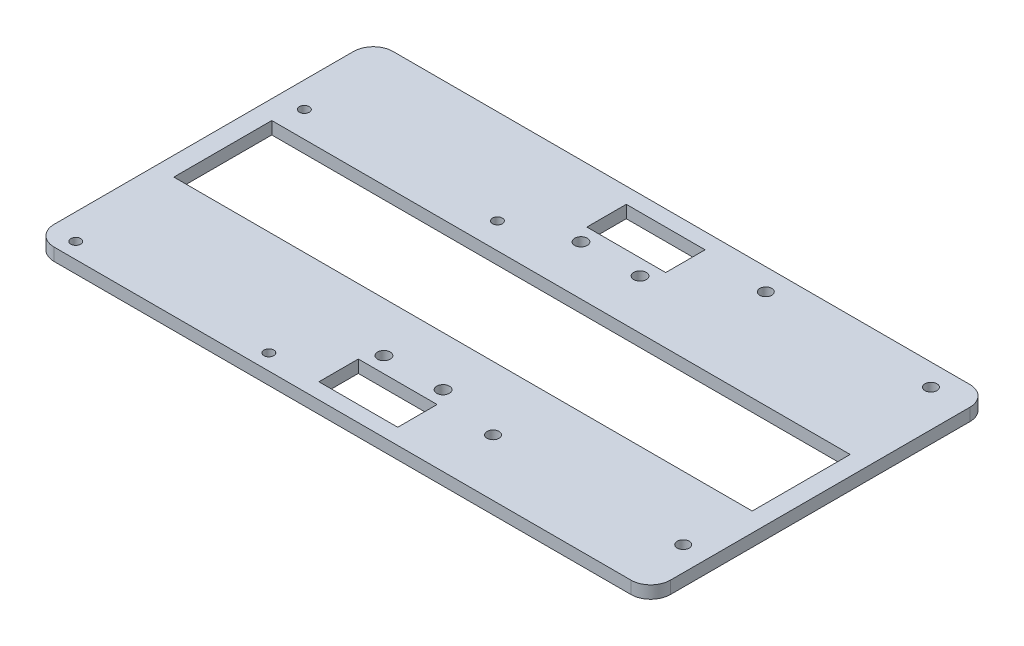
SolidWorks part; units mm, degrees
ref_plane "Front Plane" through (0, 0, 0) normal (0, 0, 1) x (1, 0, 0)
ref_plane "Top Plane" through (0, 0, 0) normal (0, 1, 0) x (1, 0, 0)
ref_plane "Right Plane" through (0, 0, 0) normal (1, 0, 0) x (0, 0, -1)
sketch "Sketch1" plane through (0, 0, 0) normal (0, 1, 0) x (1, 0, 0)
  line L1 (-78.2, 43) -> (78.2, 43)
  line L2 (-78.2, 43) -> (-78.2, -43)
  line L3 (-78.2, -43) -> (78.2, -43)
  line L4 (78.2, 43) -> (78.2, -43)
  line L5 (-78.2, 43) -> (78.2, -43) construction
  line L6 (-78.2, -43) -> (78.2, 43) construction
  point P0 (0, 0)
  dimension "D1" = 156.4
  dimension "D2" = 86
extrude "Boss-Extrude1" add sketch "Sketch1" along normal blind 3.175
sketch "Sketch3" plane through (0, 0, 0) normal (0, -1, 0) x (1, 0, 0)
  circle A0 centre (-22.7, -19) radius 1.25 construction
  circle A1 centre (-71.7, -19) radius 1.25 construction
  circle A2 centre (-71.7, 39) radius 1.25 construction
  circle A3 centre (-22.7, 39) radius 1.25 construction
  circle A4 centre (72.025, 28.575) radius 1.524 construction
  circle A5 centre (23.765, 28.575) radius 1.524 construction
  circle A6 centre (68.85, -37.465) radius 1.524 construction
  circle A7 centre (26.94, -37.465) radius 1.524 construction
  circle A8 centre (-22.7, -19) radius 1.25
  circle A9 centre (-71.7, -19) radius 1.25
  circle A10 centre (-71.7, 39) radius 1.25
  circle A11 centre (-22.7, 39) radius 1.25
  circle A12 centre (72.025, 28.575) radius 1.524
  circle A13 centre (23.765, 28.575) radius 1.524
  circle A14 centre (68.85, -37.465) radius 1.524
  circle A15 centre (26.94, -37.465) radius 1.524
extrude "Cut-Extrude2" cut sketch "Sketch3" against normal through all
sketch "Sketch4" plane through (0, 0, 0) normal (0, -1, 0) x (1, 0, 0)
  line L0 (-73.39, 12.43) -> (-73.39, -12.43) construction
  line L1 (73.39, 12.43) -> (-73.39, 12.43) construction
  line L2 (-73.39, -12.43) -> (73.39, -12.43) construction
  line L3 (73.39, -12.43) -> (73.39, 12.43) construction
  line L4 (-73.39, 12.43) -> (-73.39, -12.43)
  line L5 (73.39, 12.43) -> (-73.39, 12.43)
  line L6 (-73.39, -12.43) -> (73.39, -12.43)
  line L7 (73.39, -12.43) -> (73.39, 12.43)
extrude "Cut-Extrude3" cut sketch "Sketch4" against normal through all
sketch "Sketch5" plane through (0, 0, 0) normal (0, -1, 0) x (1, 0, 0)
  line L1 (-7.5, -25) -> (7.5, -25) construction
  line L2 (-7.5, -25) -> (-7.5, 25) construction
  line L3 (-7.5, 25) -> (7.5, 25) construction
  line L4 (7.5, -25) -> (7.5, 25) construction
  line L5 (-7.5, -25) -> (7.5, 25) construction
  line L6 (-7.5, 25) -> (7.5, -25) construction
  circle A0 centre (7.5, -25) radius 1.6
  circle A1 centre (-7.5, -25) radius 1.6
  circle A2 centre (-7.5, 25) radius 1.6
  circle A3 centre (7.5, 25) radius 1.6
  point P0 (0, 0)
  dimension "D3" = 3.2
  dimension "D1" = 15
  dimension "D2" = 50
extrude "Cut-Extrude4" cut sketch "Sketch5" against normal through all
sketch "Sketch6" plane through (0, 0, 0) normal (0, -1, 0) x (1, 0, 0)
  line L0 (5.9, 25) -> (-5.9, 25) construction
  line L1 (-5.9, 25) -> (0, 25) construction
  line L2 (0, 25) -> (0, 43) construction
  line L3 (-78.2, 43) -> (78.2, 43) construction
  line L4 (78.2, 0) -> (-78.2, 0) construction
  line L5 (10, 29) -> (-10, 29)
  line L6 (10, 29) -> (10, 39)
  line L7 (10, 39) -> (-10, 39)
  line L8 (-10, 29) -> (-10, 39)
  line L9 (10, 29) -> (-10, 39) construction
  line L10 (10, 39) -> (-10, 29) construction
  line L11 (78.2, 43) -> (78.2, -43) construction
  line L12 (-78.2, -43) -> (-78.2, 43) construction
  line L13 (10, -29) -> (-10, -29)
  line L14 (10, -29) -> (10, -39)
  line L15 (10, -39) -> (-10, -39)
  line L16 (-10, -29) -> (-10, -39)
  circle A0 centre (7.5, 25) radius 1.6 construction
  circle A1 centre (-7.5, 25) radius 1.6 construction
  point P7 (0, 34)
  dimension "D1" = 10
  dimension "D2" = 20
extrude "Cut-Extrude5" cut sketch "Sketch6" against normal through all
fillet "Fillet1" radius 5 4 edges at (-78.2, 1.5875, -43) (-78.2, 1.5875, 43) (78.2, 1.5875, -43) (78.2, 1.5875, 43)
